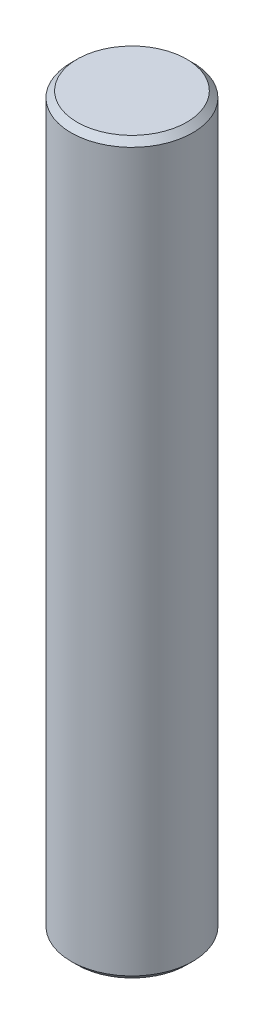
SolidWorks part; units mm, degrees
material "AISI 316 Annealed Stainless Steel Bar (SS)"
ref_plane "Front Plane" through (0, 0, 0) normal (0, 0, 1) x (1, 0, 0)
ref_plane "Top Plane" through (0, 0, 0) normal (0, 1, 0) x (1, 0, 0)
ref_plane "Right Plane" through (0, 0, 0) normal (1, 0, 0) x (0, 0, -1)
sketch "Sketch1" plane through (0, 0, 0) normal (0, 1, 0) x (1, 0, 0)
  circle A0 centre (0, 0) radius 2.5
  dimension "D1" = 5
extrude "Boss-Extrude1" add sketch "Sketch1" along normal mid plane 30
chamfer "Chamfer1" distance 0.25 angle 45 2 edges at (0, -15, 2.5) (0, 15, 2.5)
